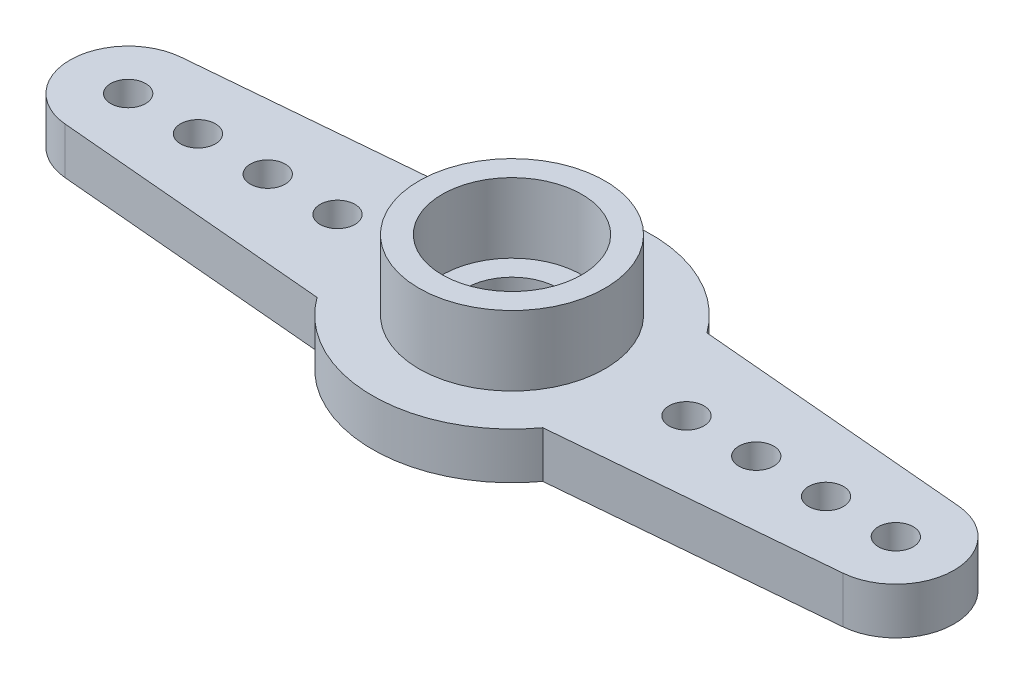
SolidWorks part; units mm, degrees
ref_plane "Front Plane" through (0, 0, 0) normal (0, 0, 1) x (1, 0, 0)
ref_plane "Top Plane" through (0, 0, 0) normal (0, 1, 0) x (1, 0, 0)
ref_plane "Right Plane" through (0, 0, 0) normal (1, 0, 0) x (0, 0, -1)
sketch "Sketch1" plane through (0, 0, 0) normal (0, 1, 0) x (1, 0, 0)
  line L0 (-19, 0) -> (19, 0) construction
  line L1 (16.7179, -2.4905) -> (4.8528, -3.5286)
  line L2 (16.7179, 2.4905) -> (4.8528, 3.5286)
  line L3 (0, -55) -> (0, 55) construction
  line L4 (-16.7179, 2.4905) -> (-4.8528, 3.5286)
  line L5 (-16.7179, -2.4905) -> (-4.8528, -3.5286)
  circle A0 centre (0, 0) radius 2
  circle A1 centre (7.5, 0) radius 0.75
  circle A2 centre (10.5, 0) radius 0.75
  circle A3 centre (13.5, 0) radius 0.75
  circle A4 centre (16.5, 0) radius 0.75
  arc A5 (4.8528, 3.5286) -> (-4.8528, 3.5286) centre (0, 0) ccw
  arc A6 (16.7179, -2.4905) -> (16.7179, 2.4905) centre (16.5, 0) ccw
  arc A7 (-16.7179, -2.4905) -> (-16.7179, 2.4905) centre (-16.5, 0) cw
  circle A8 centre (-16.5, 0) radius 0.75
  circle A9 centre (-13.5, 0) radius 0.75
  circle A10 centre (-10.5, 0) radius 0.75
  circle A11 centre (-7.5, 0) radius 0.75
  arc A12 (-4.8528, -3.5286) -> (4.8528, -3.5286) centre (0, 0) ccw
  point P4 (0, 0)
  dimension "D1" = 4
  dimension "D2" = 7.5
  dimension "D3" = 1.5
  dimension "D4" = 1.5
  dimension "D6" = 1.5
  dimension "D7" = 1.5
  dimension "D11" = 12
  dimension "D12" = 2.5
  dimension "D5" = 3
  dimension "D8" = 3
  dimension "D9" = 3
  dimension "D10" = 38
  dimension "D13" = 5
  dimension "D14" = 5
extrude "Boss-Extrude1" add sketch "Sketch1" along normal blind 2
sketch "Sketch2" plane through (0, 2, 0) normal (0, 1, 0) x (1, 0, 0)
  circle A0 centre (0, 0) radius 4
  circle A1 centre (0, 0) radius 3
  dimension "D1" = 8
  dimension "D2" = 1
extrude "Boss-Extrude2" add sketch "Sketch2" along normal blind 3
